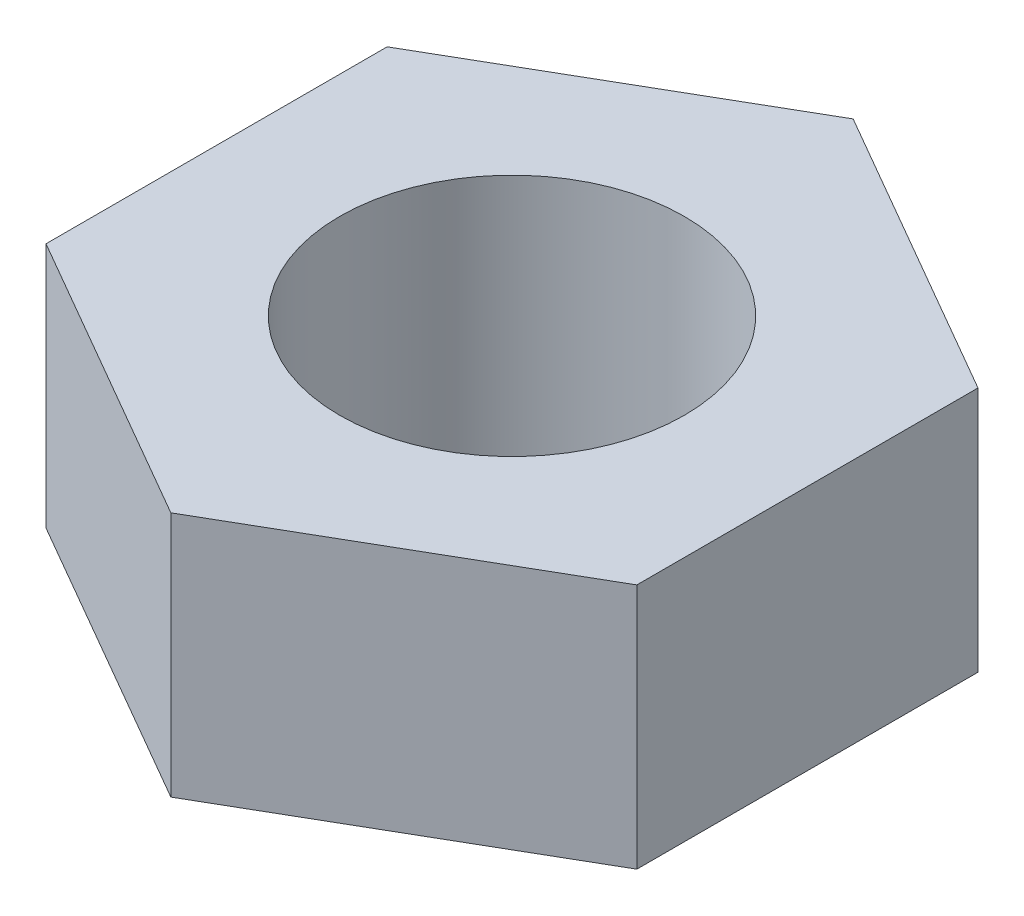
SolidWorks part; units mm, degrees
ref_plane "Front Plane" through (0, 0, 0) normal (0, 0, 1) x (1, 0, 0)
ref_plane "Top Plane" through (0, 0, 0) normal (0, 1, 0) x (1, 0, 0)
ref_plane "Right Plane" through (0, 0, 0) normal (1, 0, 0) x (0, 0, -1)
sketch "Sketch1" plane through (0, 0, 0) normal (0, 1, 0) x (1, 0, 0)
  line L1 (0, 13.8564) -> (-12, 6.9282)
  line L2 (-12, 6.9282) -> (-12, -6.9282)
  line L3 (-12, -6.9282) -> (0, -13.8564)
  line L4 (0, -13.8564) -> (12, -6.9282)
  line L5 (12, -6.9282) -> (12, 6.9282)
  line L6 (12, 6.9282) -> (0, 13.8564)
  circle A0 centre (0, 0) radius 12 construction
  dimension "D1" = 24
extrude "Boss-Extrude1" add sketch "Sketch1" along normal blind 10
sketch "Sketch2" plane through (0, 10, 0) normal (0, 1, 0) x (1, 0, 0)
  circle A0 centre (0, 0) radius 7
  dimension "D1" = 14
extrude "Cut-Extrude1" cut sketch "Sketch2" against normal blind 10
